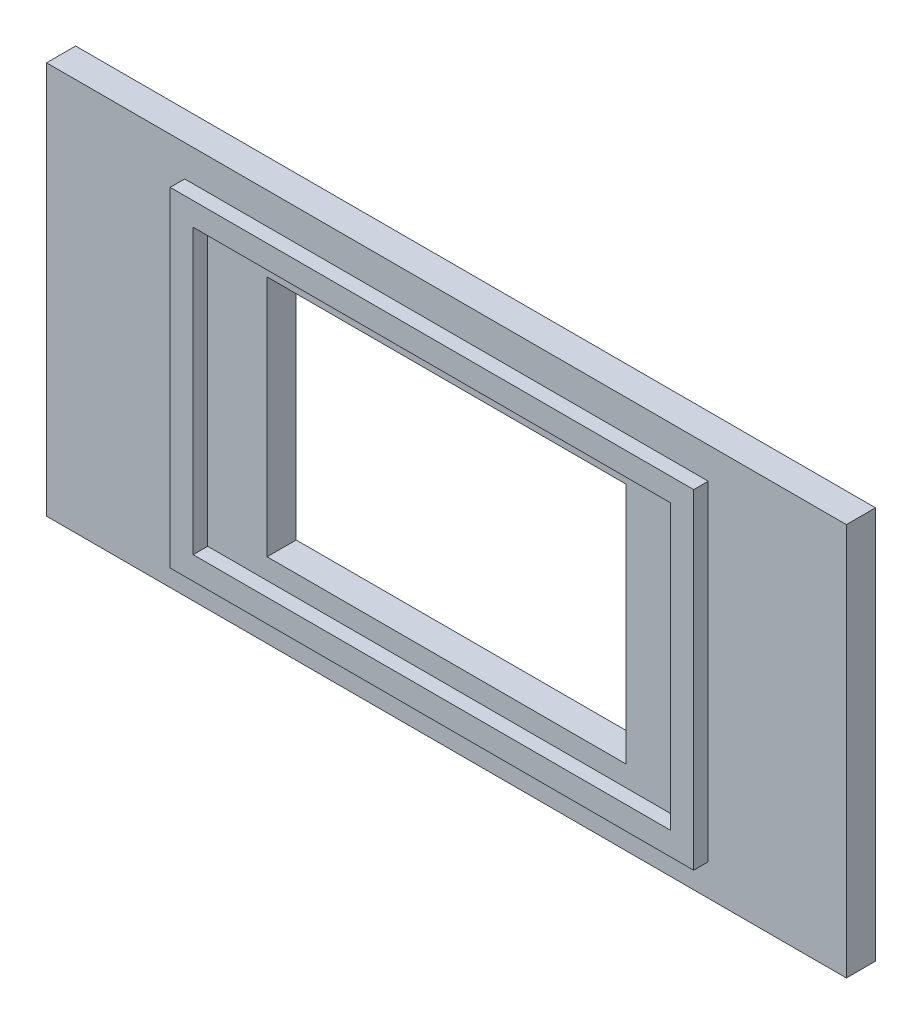
SolidWorks part; units mm, degrees
ref_plane "Front Plane" through (0, 0, 0) normal (0, 0, 1) x (1, 0, 0)
ref_plane "Top Plane" through (0, 0, 0) normal (0, 1, 0) x (1, 0, 0)
ref_plane "Right Plane" through (0, 0, 0) normal (1, 0, 0) x (0, 0, -1)
sketch "Sketch1" plane through (0, 0, 0) normal (0, 0, 1) x (1, 0, 0)
  line L1 (-82.5, -40.5) -> (82.5, -40.5)
  line L2 (-82.5, -40.5) -> (-82.5, 40.5)
  line L3 (-82.5, 40.5) -> (82.5, 40.5)
  line L4 (82.5, -40.5) -> (82.5, 40.5)
  line L6 (-37, -25) -> (37, -25)
  line L7 (-37, -25) -> (-37, 25)
  line L8 (-37, 25) -> (37, 25)
  line L9 (37, -25) -> (37, 25)
extrude "Boss-Extrude1" add sketch "Sketch1" along normal blind 6
sketch "Sketch2" plane through (0, 0, 0) normal (0, 0, 1) x (1, 0, 0)
  line L1 (-54, -34) -> (54, -34)
  line L2 (-54, -34) -> (-54, 34)
  line L3 (-54, 34) -> (54, 34)
  line L4 (54, -34) -> (54, 34)
  line L6 (-49.25, -29.25) -> (49.25, -29.25)
  line L7 (-49.25, -29.25) -> (-49.25, 29.25)
  line L8 (-49.25, 29.25) -> (49.25, 29.25)
  line L9 (49.25, -29.25) -> (49.25, 29.25)
extrude "Boss-Extrude2" add sketch "Sketch2" along normal blind 9
